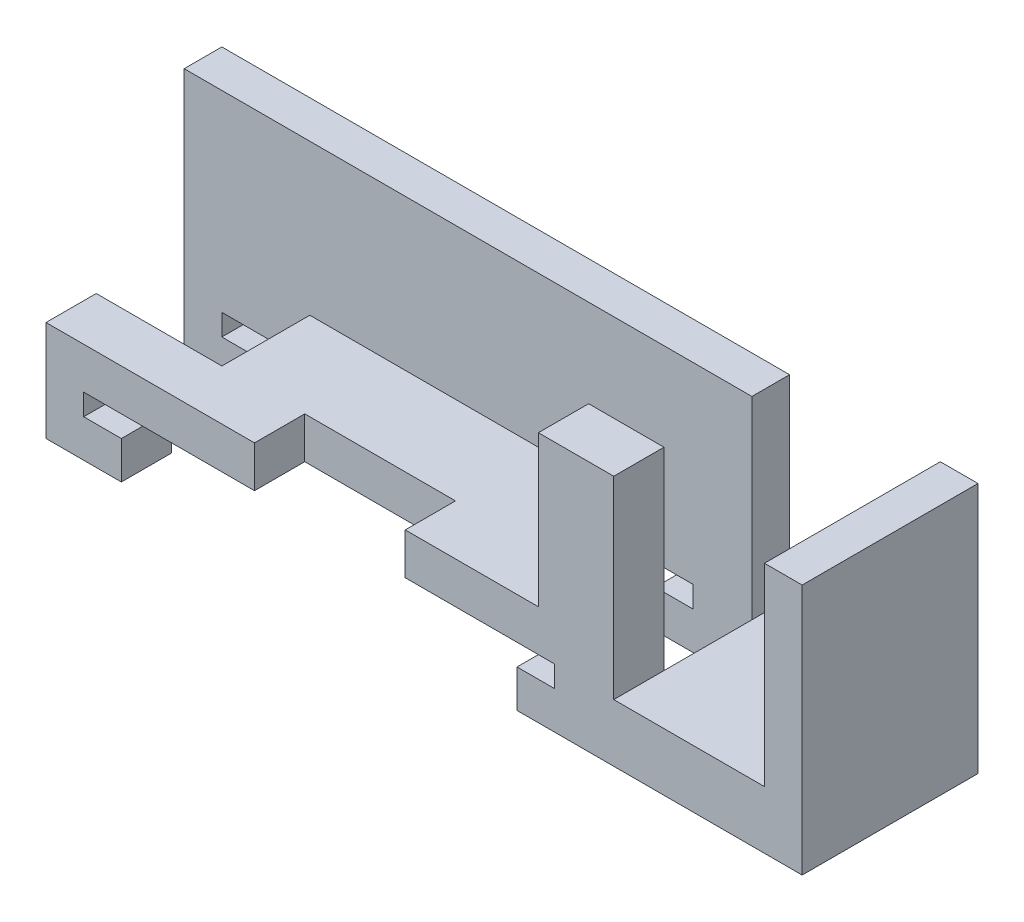
SolidWorks part; units mm, degrees
ref_plane "Alzado" through (0, 0, 0) normal (0, 0, 1) x (1, 0, 0)
ref_plane "Planta" through (0, 0, 0) normal (0, 1, 0) x (1, 0, 0)
ref_plane "Vista lateral" through (0, 0, 0) normal (1, 0, 0) x (0, 0, -1)
sketch "Croquis1" plane through (0, 0, 0) normal (0, 1, 0) x (1, 0, 0)
  line L1 (-56.1237, 20.1765) -> (4.0763, 20.1765)
  line L2 (-56.1237, 20.1765) -> (-56.1237, 6.1765)
  line L3 (-56.1237, 6.1765) -> (4.0763, 6.1765)
  line L4 (4.0763, 20.1765) -> (4.0763, 6.1765)
  dimension "D1" = 14
  dimension "D2" = 60.2
extrude "Saliente-Extruir1" add sketch "Croquis1" along normal blind 20
sketch "Croquis2" plane through (0, 0, -6.1765) normal (0, 0, 1) x (1, 0, 0)
  line L0 (-56.1237, 0) -> (4.0763, 0) construction
  line L1 (-50.1237, 0) -> (-18.6237, 0)
  line L2 (-50.1237, 3) -> (-50.1237, 0)
  line L3 (-51.0237, 4.7) -> (-20.0237, 4.7)
  line L4 (-18.6237, 3) -> (-18.6237, 0)
  line L5 (-56.1237, 20) -> (-56.1237, 0) construction
  line L10 (-53.1237, 4.7) -> (-51.0237, 4.7)
  line L11 (-53.1237, 4.7) -> (-53.1237, 3)
  line L12 (-53.1237, 3) -> (-50.1237, 3)
  line L13 (-56.1237, 20) -> (4.0763, 20) construction
  line L14 (-20.0237, 4.7) -> (-15.6237, 4.7)
  line L15 (-10.9237, 4.6) -> (1.0763, 4.6)
  line L16 (-18.6237, 3) -> (-15.6237, 3)
  line L17 (-15.6237, 4.7) -> (-15.6237, 3)
  line L18 (-10.9237, 4.6) -> (-10.9237, 20)
  line L19 (-10.9237, 20) -> (1.0763, 20)
  line L20 (1.0763, 4.6) -> (1.0763, 20)
  dimension "D2" = 37.5
  dimension "D3" = 3
  dimension "D4" = 3
  dimension "D5" = 3
  dimension "D6" = 3
  dimension "D7" = 3
  dimension "D9" = 3
  dimension "D10" = 12
extrude "Cortar-Extruir1" cut sketch "Croquis2" against normal up to vertex (14 mm away)
sketch "Croquis3" plane through (0, 20, 0) normal (0, 1, 0) x (1, 0, 0)
  line L0 (-56.1237, 20.1765) -> (-56.1237, 6.1765) construction
  line L1 (-56.1237, 17.1765) -> (-46.1237, 17.1765)
  line L2 (-56.1237, 17.1765) -> (-56.1237, 10.1765)
  line L3 (-56.1237, 10.1765) -> (-46.1237, 10.1765)
  line L4 (-46.1237, 17.1765) -> (-46.1237, 10.1765)
  line L5 (-10.9237, 20.1765) -> (-10.9237, 6.1765) construction
  line L6 (-10.9237, 17.1765) -> (-20.9237, 17.1765)
  line L7 (-10.9237, 17.1765) -> (-10.9237, 10.1765)
  line L8 (-10.9237, 10.1765) -> (-20.9237, 10.1765)
  line L9 (-20.9237, 17.1765) -> (-20.9237, 10.1765)
  dimension "D1" = 3
  dimension "D2" = 7
  dimension "D3" = 10
  dimension "D4" = 3
  dimension "D5" = 10
  dimension "D6" = 7
extrude "Cortar-Extruir2" cut sketch "Croquis3" against normal blind 20
sketch "Croquis4" plane through (0, 20, 0) normal (0, 1, 0) x (1, 0, 0)
  line L0 (-46.1237, 17.1765) -> (-20.9237, 17.1765)
  line L1 (-20.9237, 17.1765) -> (-20.9237, 10.1765)
  line L2 (-20.9237, 10.1765) -> (-16.9237, 10.1765)
  line L3 (-20.9237, 10.1765) -> (-10.9237, 10.1765) construction
  line L4 (-16.9237, 6.1765) -> (-56.1237, 6.1765)
  line L5 (-56.1237, 6.1765) -> (-56.1237, 10.1765)
  line L6 (-56.1237, 10.1765) -> (-46.1237, 10.1765)
  line L7 (-46.1237, 10.1765) -> (-46.1237, 17.1765)
  line L8 (-16.9237, 10.1765) -> (-16.9237, 6.1765)
extrude "Cortar-Extruir3" cut sketch "Croquis4" against normal blind 12
sketch "Croquis5" plane through (0, 8, 0) normal (0, 1, 0) x (1, 0, 0)
  line L0 (-56.1237, 6.1765) -> (-16.9237, 6.1765) construction
  line L1 (-39.5237, 6.1765) -> (-27.5237, 6.1765)
  line L2 (-39.5237, 6.1765) -> (-39.5237, 10.1765)
  line L3 (-39.5237, 10.1765) -> (-27.5237, 10.1765)
  line L4 (-27.5237, 6.1765) -> (-27.5237, 10.1765)
  line L5 (-46.1237, 17.1765) -> (-46.1237, 10.1765) construction
  dimension "D1" = 12
  dimension "D2" = 4
  dimension "D3" = 6.6
extrude "Cortar-Extruir4" cut sketch "Croquis5" against normal up to vertex (3.3 mm away)
